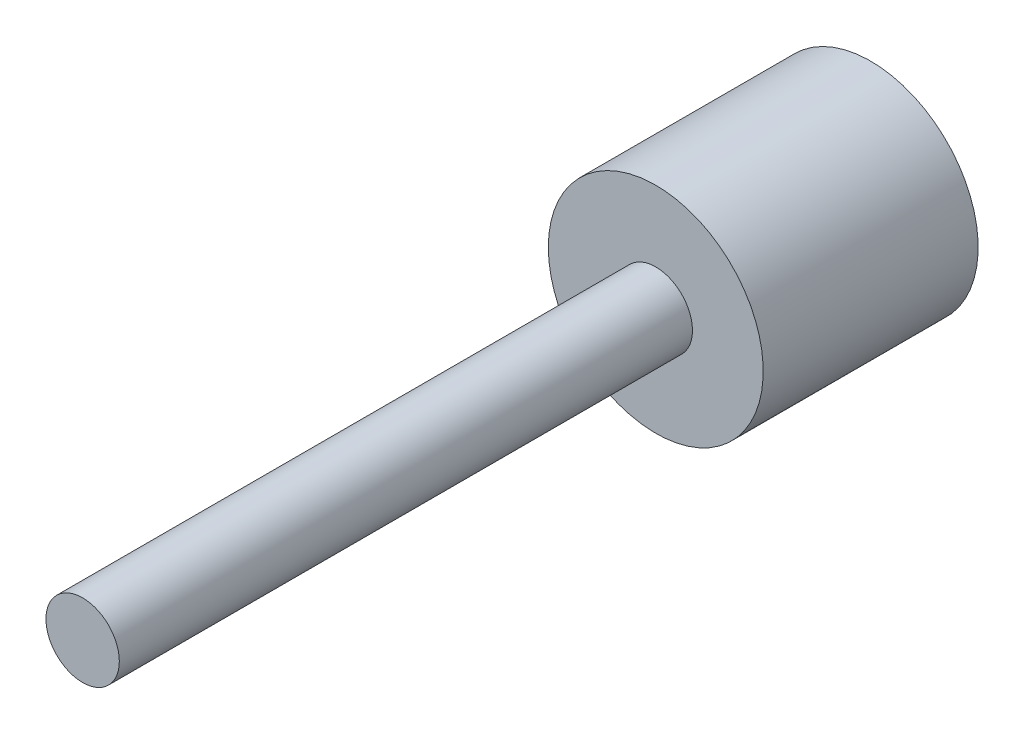
SolidWorks part; units mm, degrees
ref_plane "Front" through (0, 0, 0) normal (0, 0, 1) x (1, 0, 0)
ref_plane "Top" through (0, 0, 0) normal (0, 1, 0) x (1, 0, 0)
ref_plane "Right" through (0, 0, 0) normal (1, 0, 0) x (0, 0, -1)
sketch "Sketch2" plane through (0, 0, 0) normal (0, 0, 1) x (1, 0, 0)
  circle A0 centre (0, 0) radius 19.05
  dimension "D1" = 38.1
extrude "Boss-Extrude1" add sketch "Sketch2" along normal blind 38.1
sketch "Sketch3" plane through (0, 0, 38.1) normal (0, 0, 1) x (1, 0, 0)
  circle A0 centre (0, 0) radius 6.5053
extrude "Boss-Extrude2" add sketch "Sketch3" along normal blind 101.6
